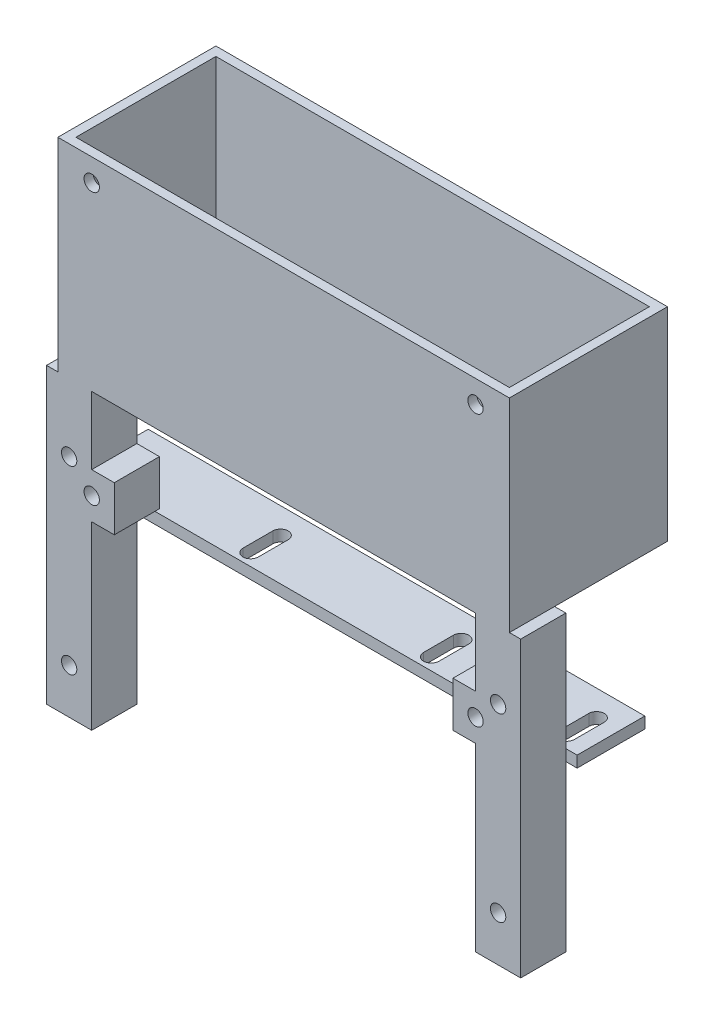
SolidWorks part; units mm, degrees
ref_plane "前视基准面" through (0, 0, 0) normal (0, 0, 1) x (1, 0, 0)
ref_plane "上视基准面" through (0, 0, 0) normal (0, 1, 0) x (1, 0, 0)
ref_plane "右视基准面" through (0, 0, 0) normal (1, 0, 0) x (0, 0, -1)
other "Configuration Table"
sketch "V3 box footprint 100 x 45 mm" plane through (0, 0, 0) normal (0, 0, 1) x (1, 0, 0)
  line L1 (-50, 0) -> (50, 0)
  line L2 (-50, 0) -> (-50, 45)
  line L3 (-50, 45) -> (50, 45)
  line L4 (50, 0) -> (50, 45)
extrude "V3 box height 35 mm" add sketch "V3 box footprint 100 x 45 mm" along normal blind 35
sketch "V3 rear opening 96 x 31 mm" plane through (0, 45, 0) normal (0, 1, 0) x (1, 0, 0)
  line L1 (-48, -2) -> (48, -2)
  line L2 (-48, -2) -> (-48, -33)
  line L3 (-48, -33) -> (48, -33)
  line L4 (48, -2) -> (48, -33)
extrude "V3 cavity all walls 2 mm" cut sketch "V3 rear opening 96 x 31 mm" against normal blind 43
sketch "V3 square beams 10 x 10 pitch 95 mm" plane through (0, 0, 0) normal (0, -1, 0) x (1, 0, 0)
  line L1 (-52.5, 25) -> (-42.5, 25)
  line L2 (-52.5, 25) -> (-52.5, 35)
  line L3 (-52.5, 35) -> (-42.5, 35)
  line L4 (-42.5, 25) -> (-42.5, 35)
  line L6 (42.5, 25) -> (52.5, 25)
  line L7 (42.5, 25) -> (42.5, 35)
  line L8 (42.5, 35) -> (52.5, 35)
  line L9 (52.5, 25) -> (52.5, 35)
extrude "V3 forward beam length 65 mm" add sketch "V3 square beams 10 x 10 pitch 95 mm" along normal blind 65
sketch "V3 left PCB ear profile" plane through (-42.5, 0, 0) normal (1, 0, 0) x (0, 0, -1)
  line L1 (-25, -25) -> (-35, -25)
  line L2 (-25, -25) -> (-25, -15)
  line L3 (-25, -15) -> (-35, -15)
  line L4 (-35, -25) -> (-35, -15)
extrude "V3 left inward ear 5 mm" add sketch "V3 left PCB ear profile" along normal blind 5
sketch "V3 right PCB ear profile" plane through (42.5, 0, 0) normal (-1, 0, 0) x (0, 0, 1)
  line L1 (25, -25) -> (35, -25)
  line L2 (25, -25) -> (25, -15)
  line L3 (25, -15) -> (35, -15)
  line L4 (35, -25) -> (35, -15)
extrude "V3 right inward ear 5 mm" add sketch "V3 right PCB ear profile" along normal blind 5
sketch "V3 PCB roof pair pitch 85 mm" plane through (0, 0, 35) normal (0, 0, 1) x (1, 0, 0)
  circle A0 centre (-42.5, 40) radius 1.7
  circle A1 centre (42.5, 40) radius 1.7
extrude "V3 M3 roof holes diameter 3.4 mm" cut sketch "V3 PCB roof pair pitch 85 mm" against normal blind 2
sketch "V3 PCB forward pair row spacing 60 mm" plane through (0, 0, 35) normal (0, 0, 1) x (1, 0, 0)
  circle A0 centre (-42.5, -20) radius 1.7
  circle A1 centre (42.5, -20) radius 1.7
extrude "V3 M3 PCB ear holes" cut sketch "V3 PCB forward pair row spacing 60 mm" against normal blind 10
sketch "V3 chassis top holes width 95 depth 40 mm" plane through (0, 0, 35) normal (0, 0, 1) x (1, 0, 0)
  circle A0 centre (-47.5, -55) radius 1.7
  circle A1 centre (-47.5, -15) radius 1.7
  circle A2 centre (47.5, -55) radius 1.7
  circle A3 centre (47.5, -15) radius 1.7
extrude "V3 M3 beam top bottom holes" cut sketch "V3 chassis top holes width 95 depth 40 mm" against normal blind 10
sketch "V3 hanging plate offset 26 thickness 2.5 mm" plane through (0, 0, 25) normal (0, 0, -1) x (-1, 0, 0)
  line L1 (55, -28.5) -> (-55, -28.5)
  line L2 (55, -28.5) -> (55, -26)
  line L3 (55, -26) -> (-55, -26)
  line L4 (-55, -28.5) -> (-55, -26)
extrude "V3 mounting plate downward 15 mm width 110" add sketch "V3 hanging plate offset 26 thickness 2.5 mm" along normal blind 15
sketch "V3 slots 6 mm below beam underside centers 20 and 50" plane through (0, -28.5, 0) normal (0, -1, 0) x (1, 0, 0)
  line L0 (-50, 15.7) -> (-50, 22.3) construction
  line L1 (-51.7, 15.7) -> (-51.7, 22.3)
  line L2 (-48.3, 15.7) -> (-48.3, 22.3)
  line L3 (-20, 15.7) -> (-20, 22.3) construction
  line L4 (-21.7, 15.7) -> (-21.7, 22.3)
  line L5 (-18.3, 15.7) -> (-18.3, 22.3)
  line L6 (20, 15.7) -> (20, 22.3) construction
  line L7 (18.3, 15.7) -> (18.3, 22.3)
  line L8 (21.7, 15.7) -> (21.7, 22.3)
  line L9 (50, 15.7) -> (50, 22.3) construction
  line L10 (48.3, 15.7) -> (48.3, 22.3)
  line L11 (51.7, 15.7) -> (51.7, 22.3)
  arc A0 (-51.7, 15.7) -> (-48.3, 15.7) centre (-50, 15.7) ccw
  arc A1 (-48.3, 22.3) -> (-51.7, 22.3) centre (-50, 22.3) ccw
  arc A2 (-21.7, 15.7) -> (-18.3, 15.7) centre (-20, 15.7) ccw
  arc A3 (-18.3, 22.3) -> (-21.7, 22.3) centre (-20, 22.3) ccw
  arc A4 (18.3, 15.7) -> (21.7, 15.7) centre (20, 15.7) ccw
  arc A5 (21.7, 22.3) -> (18.3, 22.3) centre (20, 22.3) ccw
  arc A6 (48.3, 15.7) -> (51.7, 15.7) centre (50, 15.7) ccw
  arc A7 (51.7, 22.3) -> (48.3, 22.3) centre (50, 22.3) ccw
  point P2 (-50, 19)
  point P7 (-20, 19)
  point P14 (20, 19)
  point P21 (50, 19)
  point P28 (0, 0)
  dimension "D1" = 3.4
  dimension "D2" = 6.6
  dimension "D3" = 3.4
  dimension "D4" = 6.6
  dimension "D5" = 3.4
  dimension "D6" = 6.6
  dimension "D7" = 3.4
  dimension "D8" = 6.6
extrude "V3 four mounting slots 3.4 x 10 mm" cut sketch "V3 slots 6 mm below beam underside centers 20 and 50" against normal blind 2.5
